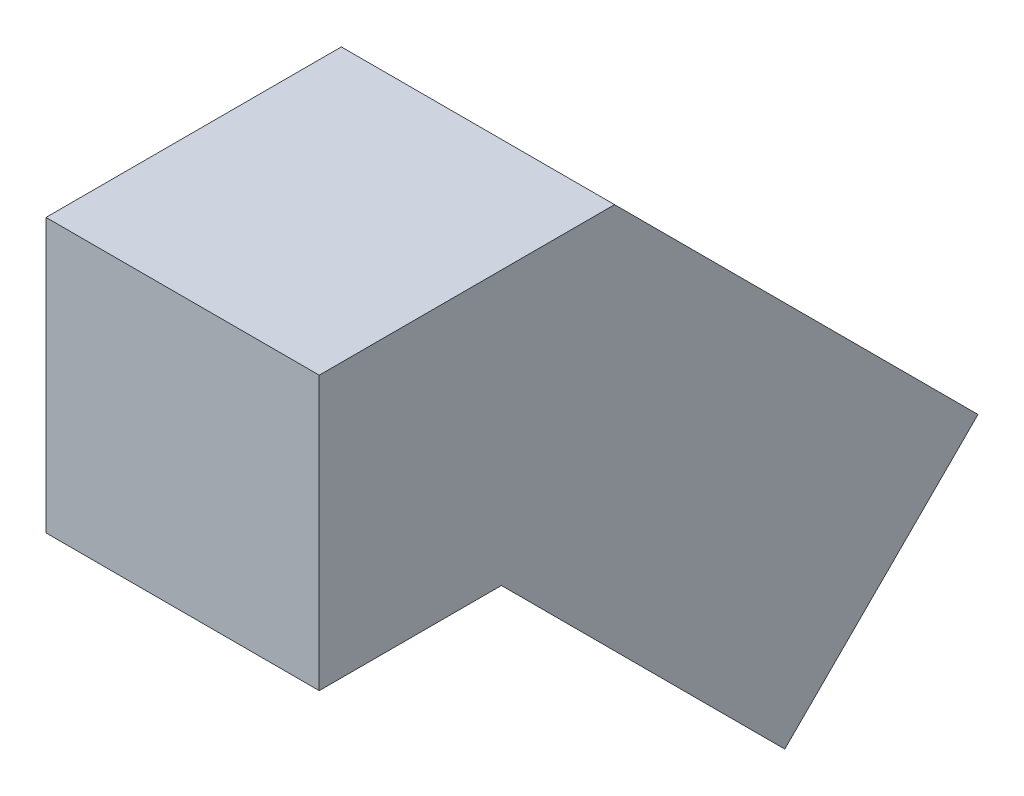
SolidWorks part; units mm, degrees
ref_plane "Front Plane" through (0, 0, 0) normal (0, 0, 1) x (1, 0, 0)
ref_plane "Top Plane" through (0, 0, 0) normal (0, 1, 0) x (1, 0, 0)
ref_plane "Right Plane" through (0, 0, 0) normal (1, 0, 0) x (0, 0, -1)
sketch "Sketch2" plane through (0, 0, 0) normal (1, 0, 0) x (0, 0, -1)
  line L0 (0, 0) -> (0, 150)
  line L1 (0, 0) -> (100, 0)
  line L2 (0, 150) -> (162.132, 150)
  line L4 (100, 0) -> (255.5635, -155.5635)
  line L5 (255.5635, -155.5635) -> (361.6295, -49.4975)
  line L6 (361.6295, -49.4975) -> (162.132, 150)
  dimension "D1" = 150
  dimension "D2" = 135
  dimension "D3" = 100
  dimension "D4" = 220
extrude "Boss-Extrude1" add sketch "Sketch2" along normal blind 150
